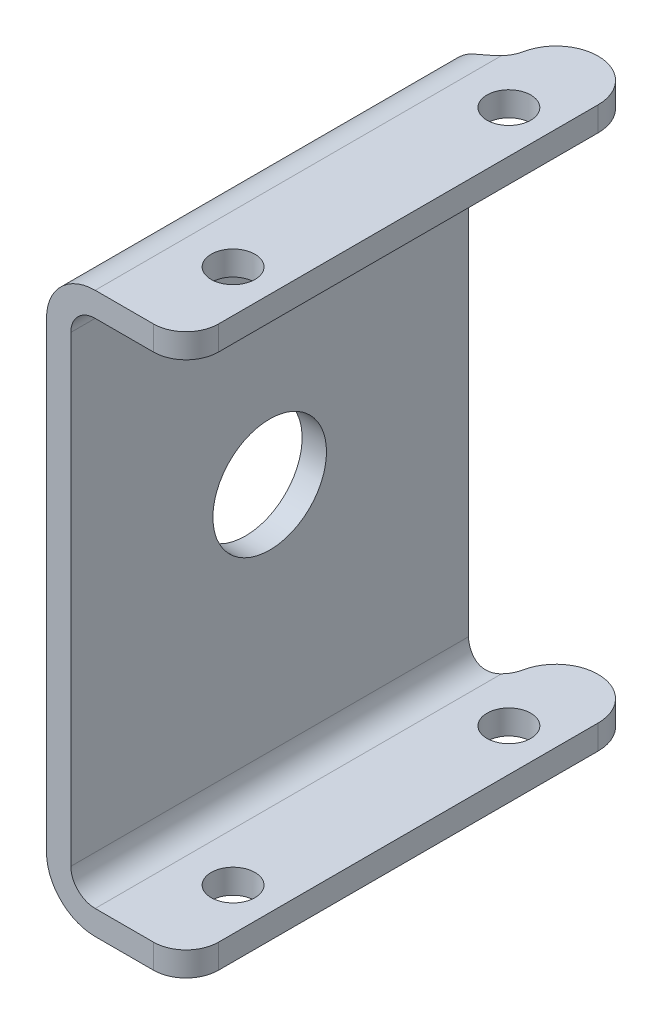
SolidWorks part; units mm, degrees
ref_plane "Ön Düzlem" through (0, 0, 0) normal (0, 0, 1) x (1, 0, 0)
ref_plane "Üst Düzlem" through (0, 0, 0) normal (0, 1, 0) x (1, 0, 0)
ref_plane "Sağ Düzlem" through (0, 0, 0) normal (1, 0, 0) x (0, 0, -1)
sketch "Sketch1" plane through (0, 0, 0) normal (0, 0, 1) x (1, 0, 0)
  line L0 (0, 0) -> (0, 34.5)
  line L1 (0, 34.5) -> (8.6, 34.5)
  line L2 (8.6, 34.5) -> (8.6, 33)
  line L3 (8.6, 33) -> (1.5, 33)
  line L4 (1.5, 33) -> (1.5, 1.5)
  line L5 (1.5, 1.5) -> (8.6, 1.5)
  line L6 (8.6, 1.5) -> (8.6, 0)
  line L7 (8.6, 0) -> (0, 0)
  dimension "D1" = 31.5
  dimension "D2" = 8.6
  dimension "D3" = 1.5
  dimension "D4" = 1.5
extrude "Boss-Extrude1" add sketch "Sketch1" along normal mid plane 28
sketch "Sketch2" plane through (0, 34.5, 0) normal (0, 1, 0) x (1, 0, 0)
  line L0 (6, 8.5) -> (6, -8.5) construction
  line L1 (0, 0) -> (6, 0) construction
  line L2 (8.6, -14) -> (8.6, 14) construction
  line L3 (1.5, -14) -> (8.6, -14) construction
  circle A0 centre (6, 8.5) radius 1.35
  circle A1 centre (6, -8.5) radius 1.35
  dimension "D2" = 2.7
  dimension "D1" = 17
  dimension "D3" = 2.6
extrude "Cut-Extrude1" cut sketch "Sketch2" against normal through all
sketch "Sketch4" plane through (0, 34.5, 0) normal (0, 1, 0) x (1, 0, 0)
  line L0 (8.6, 14) -> (0, 14) construction
  line L1 (8.6, -14) -> (8.6, 14) construction
  line L2 (6, 8.5) -> (6, 11.4) construction
  line L3 (0, -14) -> (0, 14) construction
  line L4 (1.7427, 10.5145) -> (0, 10.5145)
  line L5 (8.6, 11.4) -> (10.4287, 11.4)
  line L6 (10.4287, 11.4) -> (10.4287, 14.7089)
  line L7 (10.4287, 14.7089) -> (0, 14.7089)
  line L8 (0, 14.7089) -> (0, 10.5145)
  circle A0 centre (6, 11.4) radius 2.6
  circle A1 centre (1.7427, 12.2573) radius 1.7427
  line M3 (8.6, 14) -> (0, 14)
  line M4 (0, 14) -> (0, -14)
  line M6 (8.6, -14) -> (8.6, 14)
extrude "Cut-Extrude3" cut sketch "Sketch4" against normal through all contours A0 M6 M3 | L7 L8 L5 L6 M3 M6 | A1 A0 M3 | A1 | A1 M3 M4 | A1 L8 L4
sketch "Sketch3" plane through (0, 0, 0) normal (-1, 0, 0) x (0, 0, 1)
  line L0 (-10.5145, 17.25) -> (14, 17.25) construction
  line L2 (-10.5145, 0) -> (-10.5145, 34.5) construction
  line L3 (14, 34.5) -> (14, 0) construction
  circle A0 centre (1.7427, 17.25) radius 3.5
  dimension "D1" = 7
extrude "Cut-Extrude2" cut sketch "Sketch3" against normal through all
fillet "Fillet1" radius 3 2 edges at (0, 0, 1.7427) (0, 34.5, 1.7427)
fillet "Fillet2" radius 2 2 edges at (8.6, 0.75, 14) (8.6, 33.75, 14)
fillet "Fillet3" radius 1.5 2 edges at (1.5, 1.5, 1.7427) (1.5, 33, 1.7427)
